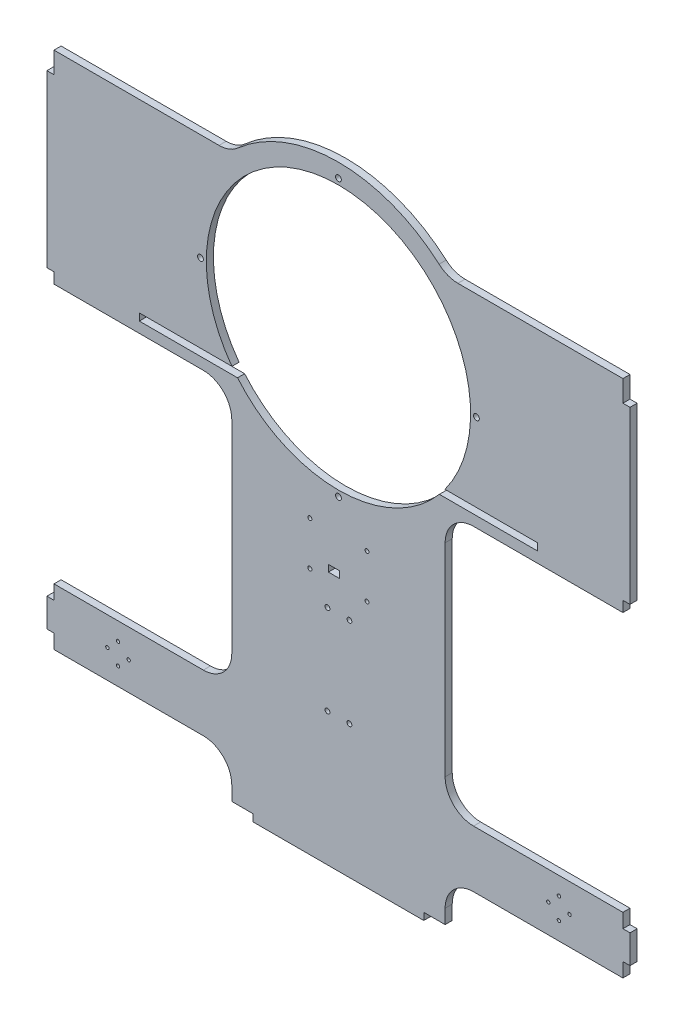
SolidWorks part; units mm, degrees
ref_plane "Front Plane" through (0, 0, 0) normal (0, 0, 1) x (1, 0, 0)
ref_plane "Top Plane" through (0, 0, 0) normal (0, 1, 0) x (1, 0, 0)
ref_plane "Right Plane" through (0, 0, 0) normal (1, 0, 0) x (0, 0, -1)
sketch "Main Body Sketch" plane through (0, 0, 0) normal (0, 0, 1) x (1, 0, 0)
  line L0 (-96.5459, -95.25) -> (-254, -95.25)
  line L1 (-254, 95.25) -> (-254, -95.25)
  line L2 (96.5459, 95.25) -> (254, 95.25)
  line L3 (254, 95.25) -> (254, -95.25)
  line L4 (254, -95.25) -> (96.5459, -95.25)
  line L5 (-96.5459, 95.25) -> (-254, 95.25)
  line L6 (-95.25, -96.5459) -> (-95.25, -406.4)
  line L7 (-95.25, -406.4) -> (95.25, -406.4)
  line L8 (95.25, -406.4) -> (95.25, -96.5459)
  circle A0 centre (0, 0) radius 117.9995
  arc A1 (-96.5459, -95.25) -> (-95.25, -96.5459) centre (0, 0) ccw
  arc A4 (96.5459, 95.25) -> (-96.5459, 95.25) centre (0, 0) ccw
  arc A5 (95.25, -96.5459) -> (96.5459, -95.25) centre (0, 0) ccw
  point P15 (0, -406.4)
  point P16 (254, 0)
  point P17 (-254, 0)
  dimension "D1" = 235.999
  dimension "D2" = 271.2466
  dimension "D3" = 95.25
  dimension "D4" = 254
  dimension "D7" = 406.4
  dimension "D11" = 190.5
extrude "Main Body" add sketch "Main Body Sketch" along normal mid plane 6.35
sketch "Tabs Sketch" plane through (0, 0, 3.175) normal (0, 0, 1) x (1, 0, 0)
  line L1 (-260.35, 76.2) -> (-254, 76.2)
  line L2 (-260.35, 76.2) -> (-260.35, -76.2)
  line L3 (-260.35, -76.2) -> (-254, -76.2)
  line L4 (-254, 76.2) -> (-254, -76.2)
  line L10 (-254, 95.25) -> (-254, -95.25) construction
  line L11 (-95.25, -406.4) -> (95.25, -406.4) construction
  line L12 (-76.2, -406.4) -> (76.2, -406.4)
  line L13 (-76.2, -406.4) -> (-76.2, -412.75)
  line L14 (-76.2, -412.75) -> (76.2, -412.75)
  line L15 (76.2, -406.4) -> (76.2, -412.75)
  point P6 (-260.35, 0)
  point P13 (0, -412.75)
  dimension "D1" = 6.35
  dimension "D2" = 6.35
  dimension "D3" = 152.4
  dimension "D4" = 152.4
extrude "Outside Tabs" add sketch "Tabs Sketch" against normal up to surface (6.35 mm away)
mirror "Outside Tabs Mirror" about plane through (0, 0, 0) normal (1, 0, 0) of "Outside Tabs"
hole_wizard "#6 (0.204) Tube Mount" positions "Sketch8" profile "Sketch9" hole size "#6" standard "ANSI Inch" end condition through all
sketch "Sketch8" plane through (0, 0, 3.175) normal (0, 0, 1) x (1, 0, 0)
  circle A0 centre (0, 0) radius 123.19
  point P5 (123.19, 0)
  point P7 (0, 123.19)
  point P9 (-123.19, 0)
  point P11 (0, -123.19)
  dimension "D1" = 246.38
sketch "Sketch9" plane through (0, -123.19, 3.175) normal (1, 0, 0) x (0, -1, 0)
  line L0 (0, 0) -> (0, 6.35)
  line L1 (0, 6.35) -> (2.5908, 6.35)
  line L2 (2.5908, 6.35) -> (2.5908, 0)
  line L5 (2.5908, 0) -> (0, 0)
  line L11 (0, -6.35) -> (0, 107.95) construction
  dimension "Thru Hole Dia." = 5.1816
  dimension "Thru Hole Depth" = 6.35
sketch "Thruster Cross Beams" plane through (0, 0, 3.175) normal (0, 0, 1) x (1, 0, 0)
  line L0 (-260.35, 76.2) -> (-260.35, -76.2) construction
  line L1 (-260.35, -57.15) -> (-203.2, -57.15)
  line L2 (-260.35, -57.15) -> (-260.35, -63.5)
  line L3 (-260.35, -63.5) -> (-203.2, -63.5)
  line L4 (-203.2, -57.15) -> (-203.2, -63.5)
  dimension "D2" = 57.15
  dimension "D3" = 6.35
  dimension "D4" = 57.15
extrude "Thruster Mounts" [suppressed] cut sketch "Thruster Cross Beams" against normal through all
mirror "Thruster Mirror" [suppressed] about plane through (0, 0, 0) normal (1, 0, 0)
sketch "Sketch11" plane through (0, 0, 3.175) normal (0, 0, 1) x (1, 0, 0)
  line L0 (-175.273, 53.95) -> (-184.773, 44.45)
  line L1 (-184.773, 44.45) -> (-175.273, 34.95)
  line L2 (-175.273, 34.95) -> (-165.773, 44.45)
  line L3 (-165.773, 44.45) -> (-175.273, 53.95)
  line L4 (-96.5459, 95.25) -> (-254, 95.25) construction
  circle A0 centre (-175.273, 53.95) radius 1.5
  circle A1 centre (-165.773, 44.45) radius 1.5
  circle A2 centre (-175.273, 34.95) radius 1.5
  circle A3 centre (-184.773, 44.45) radius 1.5
  point P11 (-175.273, 95.25)
  dimension "D2" = 3
  dimension "D1" = 19
  dimension "D3" = 50.8
extrude "Vertical Thruster Mounts" [suppressed] cut sketch "Sketch11" against normal through all contours A0 | A3 | A2 | A1
mirror "Mirror1" [suppressed] about plane through (0, 0, 0) normal (1, 0, 0)
sketch "Sketch12" plane through (0, 0, 3.175) normal (0, 0, 1) x (1, 0, 0)
  line L0 (-95.25, -96.5459) -> (-95.25, -406.4) construction
  line L1 (-95.25, -317.5) -> (-260.35, -317.5)
  line L2 (-95.25, -317.5) -> (-95.25, -368.3)
  line L3 (-95.25, -368.3) -> (-260.35, -368.3)
  line L4 (-260.35, -317.5) -> (-260.35, -368.3)
  line L6 (260.35, -317.5) -> (95.25, -317.5)
  line L7 (260.35, -317.5) -> (260.35, -368.3)
  line L8 (260.35, -368.3) -> (95.25, -368.3)
  line L9 (95.25, -317.5) -> (95.25, -368.3)
  line L10 (95.25, -406.4) -> (95.25, -96.5459) construction
  line L12 (-260.35, 76.2) -> (-260.35, -76.2) construction
  line L13 (260.35, 76.2) -> (260.35, -76.2) construction
  line M27 (95.25, -406.4) -> (95.25, -96.5459)
  line M45 (-95.25, -96.5459) -> (-95.25, -406.4)
  dimension "D1" = 50.8
  dimension "D2" = 38.1
extrude "Boss-Extrude1" add sketch "Sketch12" against normal up to surface (6.35 mm away) contours L1 L4 L3 M45 | L8 L7 L6 M27
sketch "Sketch13" plane through (0, 0, 3.175) normal (0, 0, 1) x (1, 0, 0)
  line L0 (-196.85, -333.4) -> (-206.35, -342.9)
  line L1 (-206.35, -342.9) -> (-196.85, -352.4)
  line L2 (-196.85, -352.4) -> (-187.35, -342.9)
  line L3 (-187.35, -342.9) -> (-196.85, -333.4)
  line L4 (-260.35, -317.5) -> (-260.35, -368.3) construction
  line L6 (-95.25, -368.3) -> (-260.35, -368.3) construction
  circle A0 centre (-196.85, -333.4) radius 1.5
  circle A1 centre (-187.35, -342.9) radius 1.5
  circle A2 centre (-196.85, -352.4) radius 1.5
  circle A3 centre (-206.35, -342.9) radius 1.5
  dimension "D2" = 3
  dimension "D1" = 19
  dimension "D3" = 63.5
  dimension "D4" = 25.4
extrude "Cut-Extrude1" cut sketch "Sketch13" against normal through all contours A0 | A1 | A2 | A3
mirror "Mirror2" about plane through (0, 0, 0) normal (1, 0, 0) of "Cut-Extrude1"
sketch "Sketch14" plane through (0, 0, 3.175) normal (0, 0, 1) x (1, 0, 0)
  line L1 (-260.35, -317.5) -> (-254, -317.5)
  line L2 (-260.35, -317.5) -> (-260.35, -330.2)
  line L3 (-260.35, -330.2) -> (-254, -330.2)
  line L4 (-254, -317.5) -> (-254, -330.2)
  line L5 (-260.35, -368.3) -> (-254, -368.3)
  line L6 (-260.35, -368.3) -> (-260.35, -355.6)
  line L7 (-260.35, -355.6) -> (-254, -355.6)
  line L8 (-254, -368.3) -> (-254, -355.6)
  dimension "D1" = 6.35
  dimension "D2" = 12.7
  dimension "D3" = 6.35
  dimension "D4" = 12.7
extrude "Cut-Extrude2" cut sketch "Sketch14" against normal through all
mirror "Mirror3" about plane through (0, 0, 0) normal (1, 0, 0) of "Cut-Extrude2"
sketch "Sketch15" plane through (0, 0, 3.175) normal (0, 0, 1) x (1, 0, 0)
  line L1 (-177.8, -69.85) -> (-90.0969, -69.85)
  line L2 (-177.8, -69.85) -> (-177.8, -76.2)
  line L3 (-177.8, -76.2) -> (-90.0969, -76.2)
  line L4 (-90.0969, -69.85) -> (-90.0969, -76.2)
  line L5 (-260.35, 76.2) -> (-260.35, -76.2) construction
  line L7 (177.8, -76.2) -> (90.0969, -76.2)
  line L8 (177.8, -76.2) -> (177.8, -69.85)
  line L9 (177.8, -69.85) -> (90.0969, -69.85)
  line L10 (90.0969, -76.2) -> (90.0969, -69.85)
  line L11 (-96.5459, -95.25) -> (-254, -95.25) construction
  circle A0 centre (0, 0) radius 117.9995 construction
  dimension "D1" = 6.35
  dimension "D2" = 19.05
  dimension "D3" = 82.55
extrude "Cut-Extrude3" cut sketch "Sketch15" against normal through all
sketch "Sketch16" plane through (0, 0, 3.175) normal (0, 0, 1) x (1, 0, 0)
  line L0 (-28.5, -171.8995) -> (28.5, -171.8995) construction
  line L1 (-28.5, -143.3995) -> (28.5, -143.3995)
  line L2 (-28.5, -143.3995) -> (-28.5, -200.3995)
  line L3 (-28.5, -200.3995) -> (28.5, -200.3995)
  line L4 (28.5, -143.3995) -> (28.5, -200.3995)
  line L5 (0, 135.6233) -> (0, -117.9995) construction
  line L6 (0, -3.4925) -> (0, 3.4925) construction
  line L7 (-16.145, -253.7495) -> (16.145, -253.7495) construction
  line L8 (-9, -179.8995) -> (1, -179.8995)
  line L9 (-9, -179.8995) -> (-9, -185.8995)
  line L10 (-9, -185.8995) -> (1, -185.8995)
  line L11 (1, -179.8995) -> (1, -185.8995)
  line L12 (-16.145, -206.7495) -> (16.145, -206.7495)
  line L13 (-16.145, -206.7495) -> (-16.145, -300.7495)
  line L14 (-16.145, -300.7495) -> (16.145, -300.7495)
  line L15 (16.145, -206.7495) -> (16.145, -300.7495)
  circle A0 centre (-25.5, -152.3995) radius 1.8
  circle A1 centre (-25.5, -191.3995) radius 1.8
  arc A2 (96.5459, 95.25) -> (-96.5459, 95.25) centre (0, 0) ccw construction
  circle A3 centre (0, 0) radius 117.9995 construction
  circle A4 centre (25.5, -191.3995) radius 1.8
  circle A5 centre (25.5, -152.3995) radius 1.8
  circle A6 centre (-9.795, -213.7495) radius 2.159
  circle A7 centre (-9.795, -293.7495) radius 2.159
  circle A8 centre (9.795, -213.7495) radius 2.159
  circle A9 centre (9.795, -293.7495) radius 2.159
  point P18 (0, -143.3995)
  point P33 (0, -206.7495)
  dimension "D2" = 3.6
  dimension "D13" = 4.318
  dimension "D1" = 57
  dimension "D3" = 9
  dimension "D4" = 3
  dimension "D5" = 10
  dimension "D6" = 6
  dimension "D7" = 19.5
  dimension "D8" = 14.5
  dimension "D9" = 25.4
  dimension "D10" = 94
  dimension "D11" = 32.29
  dimension "D12" = 6.35
  dimension "D14" = 40
  dimension "D15" = 6.35
extrude "Cut-Extrude4" cut sketch "Sketch16" against normal through all contours A0 | A5 | A4 | A1 | L10 L11 L8 L9 | A6 | A8 | A7 | A9
sketch "Sketch18" plane through (0, 0, 3.175) normal (0, 0, 1) x (1, 0, 0)
  line L0 (-254, -76.2) -> (-254, -95.25) construction
  line L1 (-95.25, -96.5459) -> (-254, -96.5459)
  line L2 (-95.25, -96.5459) -> (-95.25, -85.725)
  line L3 (-95.25, -85.725) -> (-254, -85.725)
  line L4 (-254, -96.5459) -> (-254, -85.725)
extrude "Cut-Extrude6" cut sketch "Sketch18" against normal through all
mirror "Mirror4" about plane through (0, 0, 0) normal (1, 0, 0) of "Cut-Extrude6"
fillet "Fillet1" radius 25.4 8 edges at (95.25, -85.725, 0) (-95.25, -85.725, 0) (-96.5459, 95.25, 0) (96.5459, 95.25, 0) (95.25, -368.3, 0) (95.25, -317.5, 0) (-95.25, -368.3, 0) (-95.25, -317.5, 0)
